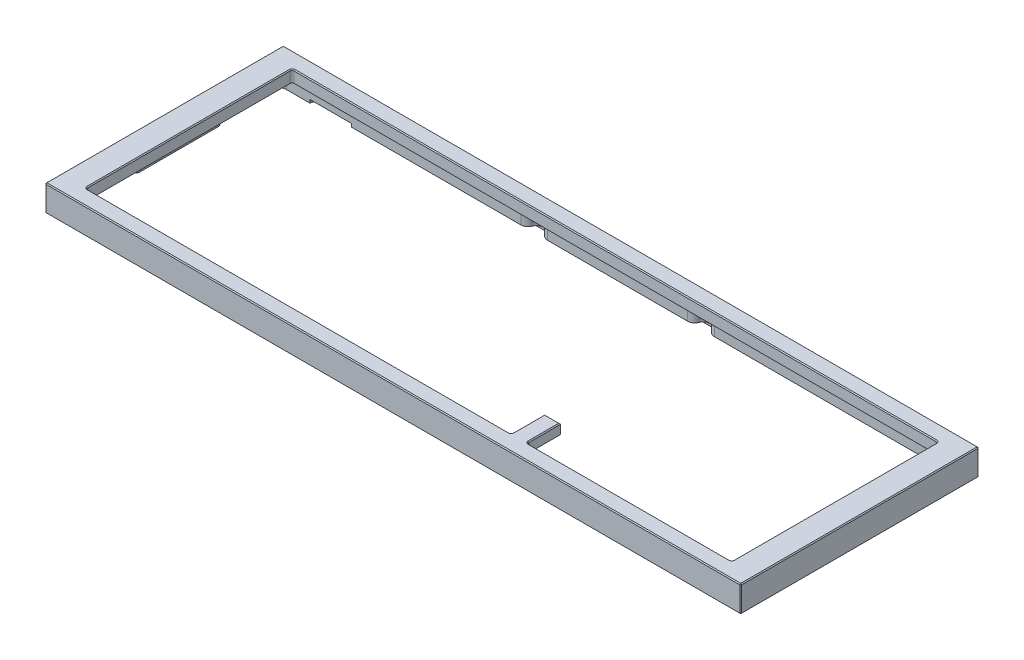
SolidWorks part; units mm, degrees
material "6061 Alloy"
ref_plane "Front Plane" through (0, 0, 0) normal (0, 0, 1) x (1, 0, 0)
ref_plane "Top Plane" through (0, 0, 0) normal (0, 1, 0) x (1, 0, 0)
ref_plane "Right Plane" through (0, 0, 0) normal (1, 0, 0) x (0, 0, -1)
sketch "Sketch1" plane through (0, 0, 0) normal (0, 1, 0) x (1, 0, 0)
  line L1 (0, 0) -> (390.8, 0)
  line L2 (0, 0) -> (0, -133.8)
  line L3 (0, -133.8) -> (390.8, -133.8)
  line L4 (390.8, 0) -> (390.8, -133.8)
  dimension "D1" = 390.8
  dimension "D2" = 133.8
extrude "Boss-Extrude1" add sketch "Sketch1" along normal blind 13.1
sketch "Sketch2" plane through (0, 13.1, 0) normal (0, 1, 0) x (1, 0, 0)
  line L0 (390.8, 0) -> (0, 0) construction
  line L1 (14, -9) -> (376.8, -9)
  line L2 (14, -9) -> (14, -124.9)
  line L3 (14, -124.9) -> (376.8, -124.9)
  line L4 (376.8, -9) -> (376.8, -124.9)
  line L5 (0, -133.8) -> (390.8, -133.8) construction
  line L6 (0, 0) -> (0, -133.8) construction
  line L7 (390.8, -133.8) -> (390.8, 0) construction
  line L8 (390.8, -133.8) -> (390.8, 0) construction
  line L9 (261.8, -124.9) -> (252.9, -124.9)
  line L10 (261.8, -124.9) -> (261.8, -106.05)
  line L11 (261.8, -106.05) -> (252.9, -106.05)
  line L12 (252.9, -124.9) -> (252.9, -106.05)
  line L13 (0, -133.8) -> (390.8, -133.8) construction
  dimension "D1" = 9
  dimension "D2" = 8.9
  dimension "D3" = 14
  dimension "D4" = 14
  dimension "D5" = 129
  dimension "D6" = 137.9
  dimension "D7" = 27.75
extrude "Cut-Extrude1" cut sketch "Sketch2" against normal through all contours L3 L12 L11 L10 L4 L1 L2
sketch "Sketch3" plane through (0, 0, 0) normal (0, -1, 0) x (1, 0, 0)
  line L0 (390.8, 0) -> (0, 0) construction
  line L1 (385.5, 2.6) -> (5.3, 2.6)
  line L2 (385.5, 2.6) -> (385.5, 131.2)
  line L3 (385.5, 131.2) -> (5.3, 131.2)
  line L4 (5.3, 2.6) -> (5.3, 131.2)
  line L5 (390.8, 133.8) -> (390.8, 0) construction
  point P4 (195.4, 2.6)
  point P7 (195.4, 0)
  point P8 (385.5, 66.9)
  point P11 (390.8, 66.9)
  dimension "D1" = 380.2
  dimension "D2" = 128.6
extrude "Cut-Extrude2" cut sketch "Sketch3" against normal blind 6.6 contours L2 L1 L4 L3
sketch "Sketch5" plane through (0, 6.6, 0) normal (0, -1, 0) x (1, 0, 0)
  line L0 (290, 128.2) -> (285, 128.2)
  line L1 (290, 128.2) -> (290, 131.2)
  line L2 (290, 131.2) -> (285, 131.2)
  line L3 (285, 128.2) -> (285, 131.2)
  line L4 (105, 128.2) -> (100, 128.2)
  line L5 (105, 128.2) -> (105, 131.2)
  line L6 (105, 131.2) -> (100, 131.2)
  line L7 (100, 128.2) -> (100, 131.2)
  line L8 (8.3, 45) -> (8.3, 88.8)
  line L9 (382.5, 45) -> (382.5, 88.8)
  line L10 (0, 133.8) -> (390.8, 133.8) construction
  line L11 (5.3, 2.6) -> (5.3, 131.2) construction
  line L12 (390.8, 0) -> (0, 0) construction
  line L13 (385.5, 2.6) -> (385.5, 131.2) construction
  line L15 (385.5, 131.2) -> (5.3, 131.2) construction
  line L16 (385.5, 131.2) -> (5.3, 131.2) construction
  line L17 (385.5, 2.6) -> (5.3, 2.6) construction
  line L18 (5.3, 2.6) -> (5.3, 131.2) construction
  circle A0 centre (102.5, 128.2) radius 2.5
  circle A1 centre (287.5, 128.2) radius 2.5
  circle A2 centre (102.5, 2.6) radius 2.5
  circle A3 centre (195.4, 2.6) radius 2.5
  circle A4 centre (287.5, 2.6) radius 2.5
  circle A5 centre (385.5, 45) radius 3
  circle A6 centre (385.5, 88.8) radius 3
  circle A7 centre (5.3, 45) radius 3
  circle A8 centre (5.3, 88.8) radius 3
  line M9 (5.3, 131.2) -> (5.3, 2.6)
  line M10 (5.3, 2.6) -> (385.5, 2.6)
  line M11 (385.5, 2.6) -> (385.5, 131.2)
  dimension "D1" = 5
  dimension "D5" = 6
  dimension "D2" = 185
  dimension "D3" = 92.9
  dimension "D4" = 185
  dimension "D6" = 45
  dimension "D7" = 97.2
  dimension "D8" = 3
  dimension "D9" = 97.2
  dimension "D10" = 45
  dimension "D11" = 45
extrude "Boss-Extrude2" add sketch "Sketch5" along normal up to surface (6.6 mm away) contours A6 L9 A5 M11 | A5 M11 | A6 M11 | A4 M10 | A3 M10 | A2 M10 | A7 M9 | A8 A7 L8 M9 | A8 M9 | A0 | L7 L6 L5 L4 | L3 L2 L1 L0 | A1 up to face at (195.4, 0, 66.9)
sketch "Sketch6" plane through (0, 6.6, 0) normal (0, -1, 0) x (-1, 0, 0)
  line L0 (-195.4, 0) -> (-195.4, -133.8) construction
  line L1 (-390.8, 0) -> (0, 0) construction
  line L2 (0, -133.8) -> (-390.8, -133.8) construction
  line L3 (-390.8, -66.9) -> (0, -66.9) construction
  line L4 (-390.8, -133.8) -> (-390.8, 0) construction
  line L5 (0, 0) -> (0, -133.8) construction
  line L6 (-285, -2.6) -> (-197.9, -2.6) construction
  line L7 (-385.5, -2.6) -> (-385.5, -42) construction
  line L8 (-385.5, -2.6) -> (-385.5, -42) construction
  point P12 (-382.9, -22.7)
  point P13 (-382.9, -111)
  point P14 (-324.8, -129)
  point P15 (-192.2, -129)
  point P16 (-148.6, -5.4)
  point P18 (-64.4, -129)
  point P19 (-7.9, -111)
  point P20 (-7.9, -22.7)
  point P22 (-242.3, -5.4)
  dimension "D1" = 22.8
  dimension "D2" = 22.7
  dimension "D3" = 7.9
  dimension "D4" = 66
  dimension "D5" = 4.8
  dimension "D6" = 198.6
  dimension "D7" = 326.4
  dimension "D8" = 2.8
  dimension "D9" = 143.2
  dimension "D10" = 236.9
sketch "Sketch7" plane through (0, 0, 0) normal (0, -1, 0) x (1, 0, 0)
  arc A0 (382.5, 45) -> (385.5, 42) centre (385.5, 45) ccw construction
  arc A1 (385.5, 91.8) -> (382.5, 88.8) centre (385.5, 88.8) ccw construction
  arc A2 (290, 2.6) -> (285, 2.6) centre (287.5, 2.6) ccw construction
  arc A3 (197.9, 2.6) -> (192.9, 2.6) centre (195.4, 2.6) ccw construction
  arc A4 (105, 2.6) -> (100, 2.6) centre (102.5, 2.6) ccw construction
  arc A5 (5.3, 42) -> (8.3, 45) centre (5.3, 45) ccw construction
  arc A6 (8.3, 88.8) -> (5.3, 91.8) centre (5.3, 88.8) ccw construction
  arc A7 (100, 128.2) -> (105, 128.2) centre (102.5, 128.2) ccw construction
  arc A8 (285, 128.2) -> (290, 128.2) centre (287.5, 128.2) ccw construction
  point P0 (385.5, 45)
  point P1 (385.5, 88.8)
  point P2 (287.5, 128.2)
  point P3 (102.5, 128.2)
  point P4 (5.3, 88.8)
  point P5 (5.3, 45)
  point P6 (102.5, 2.6)
  point P7 (195.4, 2.6)
  point P8 (287.5, 2.6)
sketch "Sketch8" plane through (0, 6.6, 0) normal (0, -1, 0) x (1, 0, 0)
  line L1 (261.8, 106.05) -> (252.9, 106.05)
  line L2 (261.8, 106.05) -> (261.8, 124.9)
  line L3 (261.8, 124.9) -> (252.9, 124.9)
  line L4 (252.9, 106.05) -> (252.9, 124.9)
extrude "Cut-Extrude3" cut sketch "Sketch8" against normal blind 1
hole_wizard "M2x0.4 Tapped Hole2" positions "3DSketch3" profile "Sketch11" tap size "M2x0.4" standard "ANSI Metric"
sketch3d "3DSketch3"
  point P0 (382.9, 6.6, 22.7)
  point P3 (382.9, 6.6, 111)
  point P6 (324.8, 6.6, 129)
  point P9 (192.2, 6.6, 129)
  point P12 (64.4, 6.6, 129)
  point P15 (7.9, 6.6, 22.7)
  point P18 (7.9, 6.6, 111)
  point P22 (242.3, 6.6, 5.4)
  point P25 (148.6, 6.6, 5.4)
sketch "Sketch11" plane through (382.9, 6.6, 22.7) normal (1, 0, 0) x (0, 0, -1)
  line L0 (0, 0) -> (0, 4.4807)
  line L1 (0, 4.4807) -> (0.8, 4)
  line L2 (0.8, 4) -> (0.8, 0)
  line L5 (0.8, 0) -> (0, 0)
  line L10 (0, 4.4807) -> (-0.8, 4) construction
  line L11 (0, -6.35) -> (0, 107.95) construction
  dimension "Tap Drill Dia." = 1.6
  dimension "Tap Drill Depth" = 4
  dimension "Drill Angle" = 118
cosmetic thread "Hole Thread10" parameters "D1"=4, "D2"=2
cosmetic thread "Hole Thread11" parameters "D1"=4, "D2"=2
cosmetic thread "Hole Thread12" parameters "D1"=4, "D2"=2
cosmetic thread "Hole Thread13" parameters "D1"=4, "D2"=2
cosmetic thread "Hole Thread14" parameters "D1"=4, "D2"=2
cosmetic thread "Hole Thread15" parameters "D1"=4, "D2"=2
cosmetic thread "Hole Thread16" parameters "D1"=4, "D2"=2
cosmetic thread "Hole Thread17" parameters "D1"=4, "D2"=2
cosmetic thread "Hole Thread18" parameters "D1"=4, "D2"=2
fillet "Fillet1" radius 4 12 edges at (385.5, 3.3, 42) (385.5, 3.3, 2.6) (5.3, 3.3, 2.6) (5.3, 3.3, 42) (5.3, 3.3, 91.8) (5.3, 3.3, 131.2) (100, 3.3, 131.2) (105, 3.3, 131.2) (290, 3.3, 131.2) (285, 3.3, 131.2) (385.5, 3.3, 131.2) (385.5, 3.3, 91.8)
fillet "Fillet2" radius 1.1 12 edges at (376.8, 9.85, 9) (376.8, 9.85, 124.9) (14, 9.85, 124.9) (14, 9.85, 9) (100, 3.3, 2.6) (105, 3.3, 2.6) (192.9, 3.3, 2.6) (197.9, 3.3, 2.6) (285, 3.3, 2.6) (290, 3.3, 2.6) (261.8, 10.35, 124.9) (252.9, 10.35, 124.9)
sketch "Sketch14" plane through (0, 0, 0) normal (0, -1, 0) x (1, 0, 0)
  line L0 (390.8, 0) -> (0, 0) construction
  line L1 (388.8, 0) -> (2, 0)
  line L2 (388.8, 0) -> (388.8, 131.8)
  line L3 (388.8, 131.8) -> (2, 131.8)
  line L4 (2, 0) -> (2, 131.8)
  line L5 (0, 0) -> (0, 133.8) construction
  line L6 (390.8, 133.8) -> (390.8, 0) construction
  line L7 (0, 133.8) -> (390.8, 133.8) construction
  line L9 (390.8, 0) -> (0, 0)
  line L10 (390.8, 0) -> (390.8, 133.8)
  line L11 (390.8, 133.8) -> (0, 133.8)
  line L12 (0, 0) -> (0, 133.8)
  line L13 (390.8, 0) -> (0, 0)
  line L14 (390.8, 0) -> (390.8, 2)
  line L15 (390.8, 2) -> (0, 2)
  line L16 (0, 0) -> (0, 2)
  dimension "D1" = 2
  dimension "D2" = 2
  dimension "D3" = 2
  dimension "D4" = 2
extrude "Boss-Extrude3" add sketch "Sketch14" along normal blind 1.7
sketch "Sketch16" plane through (0, 6.6, 0) normal (0, -1, 0) x (1, 0, 0)
  line L0 (5.3, 6.6) -> (5.3, 39.2554) construction
  line L1 (385.5, 2.6) -> (5.3, 2.6)
  line L2 (385.5, 2.6) -> (385.5, 7.6)
  line L3 (385.5, 7.6) -> (5.3, 7.6)
  line L4 (5.3, 2.6) -> (5.3, 7.6)
  line L5 (385.5, 6.6) -> (385.5, 39.2554) construction
  line L6 (381.5, 2.6) -> (290.9278, 2.6) construction
  line L7 (246.3, 6.4) -> (246.3, 7.6)
  line L8 (238.3, 6.4) -> (238.3, 7.6)
  line L9 (152.6, 6.4) -> (152.6, 7.6)
  line L10 (144.6, 6.4) -> (144.6, 7.6)
  circle A0 centre (242.3, 6.4) radius 4
  circle A1 centre (148.6, 6.4) radius 4
  point P24 (242.3, 5.4)
  point P26 (148.6, 5.4)
  dimension "D2" = 8
  dimension "D1" = 5
  dimension "D3" = 1.2
  dimension "D4" = 1.2
extrude "Boss-Extrude4" add sketch "Sketch16" along normal up to surface (6.6 mm away) contours A0 L1 L2 L3 L7 | A1 L1 A0 L8 L3 L9 | A1 L10 L3 L4 L1 up to face at (195.4, 0, 66.9)
sketch "Sketch17" plane through (0, 6.6, 0) normal (0, -1, 0) x (1, 0, 0)
  circle A0 centre (148.6, 5.4) radius 3
  circle A1 centre (242.3, 5.4) radius 3
  arc A2 (149.849, 2.6) -> (152.6, 6.4) centre (148.6, 6.4) ccw construction
extrude "Cut-Extrude5" cut sketch "Sketch17" along normal up to surface (6.6 mm away) up to face at (195.3316, 0, 64.1007)
sketch "Sketch18" plane through (0, 0, 0) normal (0, 0, -1) x (-1, 0, 0)
  line L0 (0, -1.7) -> (-390.8, -1.7) construction
  line L1 (-40.3, -1.7) -> (-28.3, -1.7)
  line L2 (-40.3, -1.7) -> (-40.3, 1.8)
  line L3 (-40.3, 1.8) -> (-28.3, 1.8)
  line L4 (-28.3, -1.7) -> (-28.3, 1.8)
  line L5 (0, 13.1) -> (0, -1.7) construction
  point P6 (-34.3, 1.8)
  dimension "D1" = 12
  dimension "D2" = 3.5
  dimension "D3" = 34.3
extrude "Cut-Extrude6" cut sketch "Sketch18" against normal blind 10
fillet "Fillet4" radius 4 4 edges at (144.6, 3.3, 7.6) (152.6, 3.3, 7.6) (238.3, 3.3, 7.6) (246.3, 3.3, 7.6)
hole_wizard "M2x0.4 Tapped Hole3" positions "3DSketch2" profile "Sketch10" tap size "M2x0.4" standard "ANSI Metric"
sketch3d "3DSketch2"
  line L0 (390.8, -1.7, 0) -> (390.8, -1.7, 133.8) construction
  line L1 (0, -1.7, 133.8) -> (0, -1.7, 0) construction
  line L7 (388.8, 0, 2) -> (40.3, 0, 2) construction
  point P0 (385.5, 0, 45)
  point P3 (385.5, 0, 88.8)
  point P6 (287.5, 0, 128.2)
  point P9 (102.5, 0, 128.2)
  point P12 (5.3, 0, 88.8)
  point P15 (5.3, 0, 45)
  point P30 (312.8185, 0, 4.3)
  point P32 (195.4074, 0, 4.3)
  point P34 (77.9815, 0, 4.3)
  dimension "D1" = 78
  dimension "D2" = 78
  dimension "D3" = 195.4
  dimension "D4" = 2.3
sketch "Sketch10" plane through (385.5, 0, 45) normal (1, 0, 0) x (0, 0, -1)
  line L0 (0, 0) -> (0, 4.4807)
  line L1 (0, 4.4807) -> (0.8, 4)
  line L2 (0.8, 4) -> (0.8, 0)
  line L5 (0.8, 0) -> (0, 0)
  line L10 (0, 4.4807) -> (-0.8, 4) construction
  line L11 (0, -6.35) -> (0, 107.95) construction
  dimension "Tap Drill Dia." = 1.6
  dimension "Tap Drill Depth" = 4
  dimension "Drill Angle" = 118
cosmetic thread "Hole Thread4" parameters "D1"=4, "D2"=2
cosmetic thread "Hole Thread5" parameters "D1"=4, "D2"=2
cosmetic thread "Hole Thread6" parameters "D1"=4, "D2"=2
cosmetic thread "Hole Thread7" parameters "D1"=4, "D2"=2
cosmetic thread "Hole Thread8" parameters "D1"=4, "D2"=2
cosmetic thread "Hole Thread9" parameters "D1"=4, "D2"=2
cosmetic thread "Hole Thread19" parameters "D1"=4, "D2"=2
cosmetic thread "Hole Thread20" parameters "D1"=4, "D2"=2
cosmetic thread "Hole Thread21" parameters "D1"=4, "D2"=2
fillet "Fillet5" radius 4 6 edges at (5.3, 3.3, 7.6) (385.5, 3.3, 7.6) (388.8, -0.85, 2) (388.8, -0.85, 131.8) (2, -0.85, 131.8) (2, -0.85, 2)
sketch "Sketch20" plane through (0, 0, 0) normal (0, -1, 0) x (1, 0, 0)
  line L2 (40.3, 2) -> (40.3, 7.6)
  line L3 (40.3, 7.6) -> (45.9, 7.6)
  line L4 (28.3, 2) -> (28.3, 7.6)
  line L5 (28.3, 7.6) -> (22.7, 7.6)
  line L6 (384.8, 2) -> (40.3, 2) construction
  circle A0 centre (40.3, 7.6) radius 5.6
  circle A1 centre (28.3, 7.6) radius 5.6
extrude "Cut-Extrude7" cut sketch "Sketch20" against normal up to surface (1.8 mm away) contours L2 A0 L3 | L5 A1 L4 up to face at (34.3, 1.8, 3.8)
chamfer "Chamfer1" distance 0.5 angle 45 27 edges at (14.15, -1.7, 0) (195.4, 13.1, 0) (0, -1.7, 66.9) (0, 13.1, 66.9) (195.4, 13.1, 133.8) (195.4, -1.7, 133.8) (390.8, -1.7, 66.9) (390.8, 13.1, 66.9) (215.55, -1.7, 0) (252.5778, 13.1, 124.5778) (252.9, 13.1, 114.925) (257.35, 13.1, 106.05) (261.8, 13.1, 114.925) (262.1222, 13.1, 124.5778) (319.3, 13.1, 124.9) (376.4778, 13.1, 124.5778) (376.8, 13.1, 66.95) (376.4778, 13.1, 9.3222) (195.4, 13.1, 9) (14.3222, 13.1, 9.3222) (14, 13.1, 66.95) (14.3222, 13.1, 124.5778) (133.45, 13.1, 124.9) (0, 5.7, 0) (0, 5.7, 133.8) (390.8, 5.7, 133.8) (390.8, 5.7, 0)
